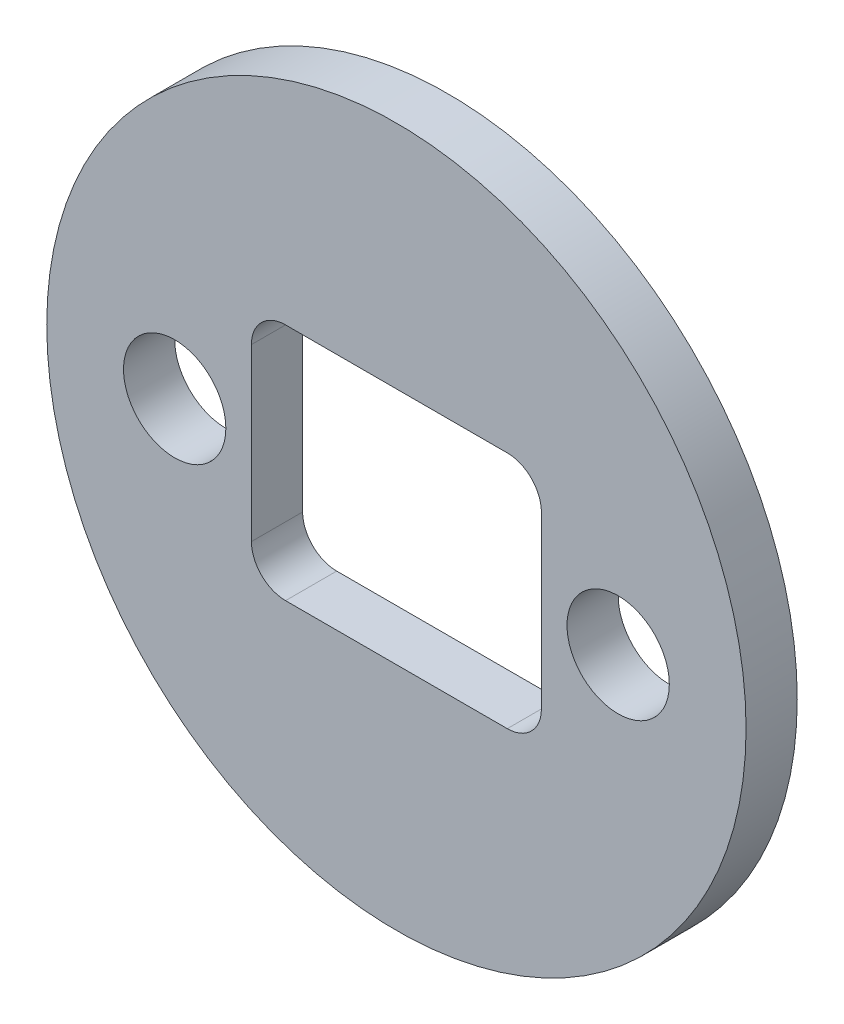
SolidWorks part; units mm, degrees
material "Acrylic (Medium-high impact)"
ref_plane "Front Plane" through (0, 0, 0) normal (0, 0, 1) x (1, 0, 0)
ref_plane "Top Plane" through (0, 0, 0) normal (0, 1, 0) x (1, 0, 0)
ref_plane "Right Plane" through (0, 0, 0) normal (1, 0, 0) x (0, 0, -1)
sketch "Sketch1" plane through (0, 0, 0) normal (0, 0, 1) x (1, 0, 0)
  line L0 (0, 20.5) -> (0, -20.5) construction
  line L1 (-8.5, 7) -> (8.5, 7)
  line L2 (-8.5, 7) -> (-8.5, -7)
  line L3 (-8.5, -7) -> (8.5, -7)
  line L4 (8.5, 7) -> (8.5, -7)
  line L5 (-8.5, 7) -> (8.5, -7) construction
  line L6 (-8.5, -7) -> (8.5, 7) construction
  circle A0 centre (0, 0) radius 20.5
  circle A1 centre (-13, 0) radius 3
  circle A2 centre (13, 0) radius 3
  dimension "D1" = 41
  dimension "D2" = 14
  dimension "D3" = 17
  dimension "D4" = 13
  dimension "D5" = 6
extrude "Boss-Extrude1" add sketch "Sketch1" along normal blind 3
fillet "Fillet1" radius 2 4 edges at (-8.5, -7, 1.5) (8.5, -7, 1.5) (-8.5, 7, 1.5) (8.5, 7, 1.5)
equation "\"D1@Sketch1\"=40.8+\"cut_free@Parameters@FabricationParameters.sldprt\""
